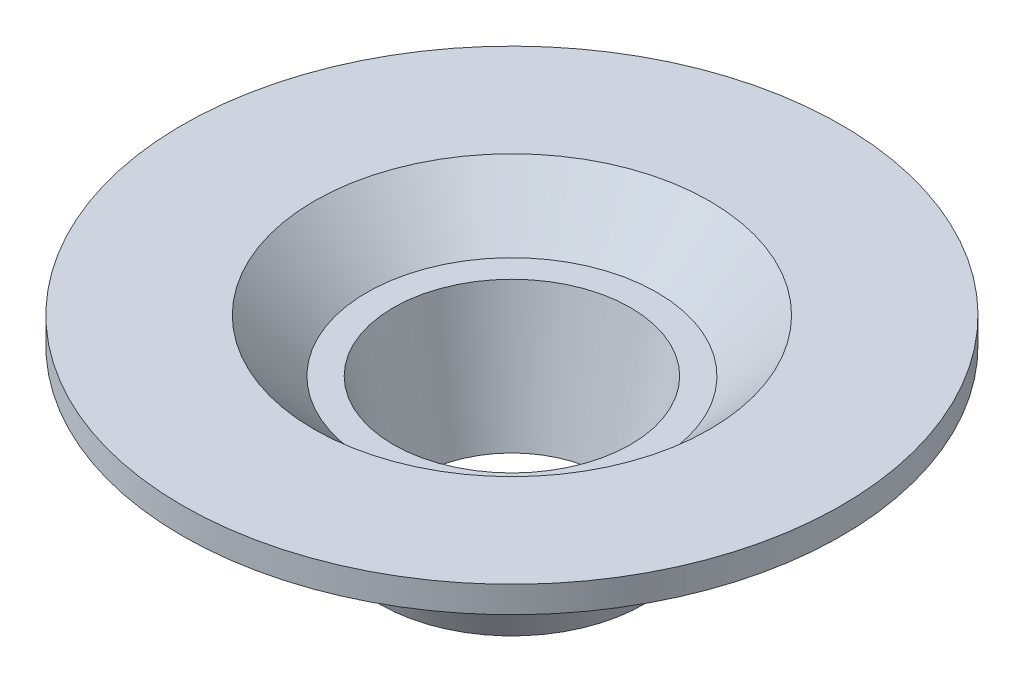
SolidWorks part; units mm, degrees
material "Brass"
ref_plane "Front Plane" through (0, 0, 0) normal (0, 0, 1) x (1, 0, 0)
ref_plane "Top Plane" through (0, 0, 0) normal (0, 1, 0) x (1, 0, 0)
ref_plane "Right Plane" through (0, 0, 0) normal (1, 0, 0) x (0, 0, -1)
sketch "Sketch1" plane through (0, 0, 0) normal (1, 0, 0) x (0, 0, -1)
  line L0 (0, 0) -> (0, -7.5388) construction
  line L1 (14, -20) -> (18, 0)
  line L2 (18, 0) -> (22, 0)
  line L3 (22, 0) -> (30, 8)
  line L4 (30, 8) -> (50, 8)
  line L5 (50, 8) -> (50, 4)
  line L7 (34, -4) -> (26, -4)
  line L8 (26, -4) -> (20, -20)
  line L9 (20, -20) -> (14, -20)
  line L10 (34, -4) -> (42, 4)
  line L11 (42, 4) -> (50, 4)
  dimension "D1" = 20
  dimension "D2" = 50
  dimension "D3" = 6
  dimension "D4" = 14
  dimension "D5" = 18
  dimension "D6" = 16
  dimension "D7" = 26
  dimension "D8" = 8
  dimension "D9" = 8
  dimension "D10" = 4
  dimension "D11" = 8
  dimension "D12" = 4
revolve "Revolve1" add sketch "Sketch1" angle 360 about L0
